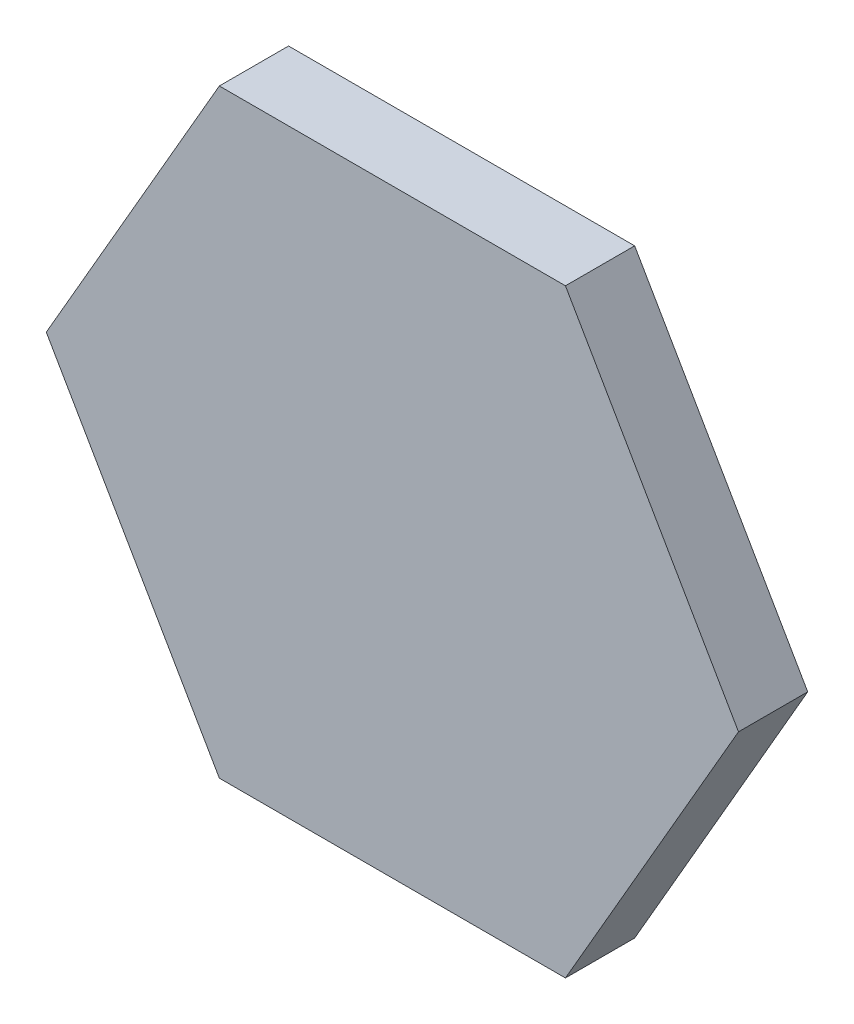
SolidWorks part; units mm, degrees
ref_plane "Plan de face" through (0, 0, 0) normal (0, 0, 1) x (1, 0, 0)
ref_plane "Plan de dessus" through (0, 0, 0) normal (0, 1, 0) x (1, 0, 0)
ref_plane "Plan de droite" through (0, 0, 0) normal (1, 0, 0) x (0, 0, -1)
sketch "Esquisse1" plane through (0, 0, 0) normal (0, 0, 1) x (1, 0, 0)
  line L1 (37.5, -64.9519) -> (75, 0)
  line L2 (75, 0) -> (37.5, 64.9519)
  line L3 (37.5, 64.9519) -> (-37.5, 64.9519)
  line L4 (-37.5, 64.9519) -> (-75, 0)
  line L5 (-75, 0) -> (-37.5, -64.9519)
  line L6 (-37.5, -64.9519) -> (37.5, -64.9519)
  circle A0 centre (0, 0) radius 75 construction
  point P1 (38.0866, 64.6097)
  dimension "D1" = 150
extrude "Boss.-Extru.1" add sketch "Esquisse1" along normal blind 15
